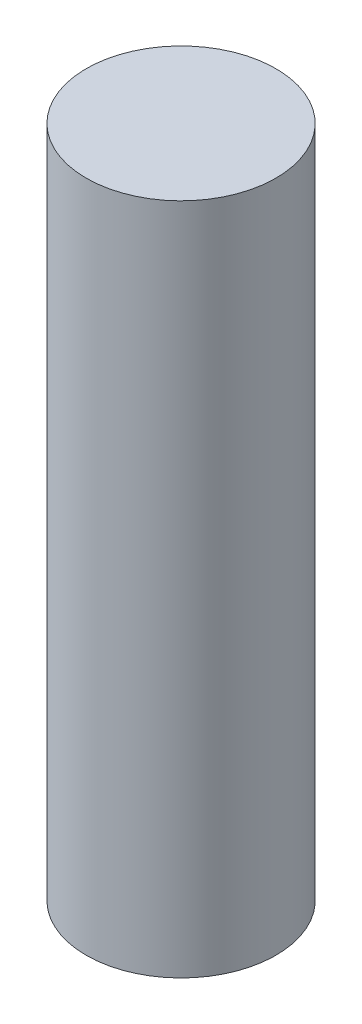
SolidWorks part; units mm, degrees
ref_plane "Front Plane" through (0, 0, 0) normal (0, 0, 1) x (1, 0, 0)
ref_plane "Top Plane" through (0, 0, 0) normal (0, 1, 0) x (1, 0, 0)
ref_plane "Right Plane" through (0, 0, 0) normal (1, 0, 0) x (0, 0, -1)
sketch "Sketch1" plane through (0, 0, 0) normal (0, 1, 0) x (1, 0, 0)
  circle A0 centre (0, 0) radius 4.75
  dimension "D1" = 9.5
extrude "Boss-Extrude1" add sketch "Sketch1" along normal blind 33.7
sketch "Sketch2" plane through (0, 0, 0) normal (0, -1, 0) x (1, 0, 0)
  circle A0 centre (0, 0) radius 3.25
  circle A1 centre (0, 0) radius 4.75 construction
  dimension "D1" = 1.5
extrude "Cut-Extrude1" cut sketch "Sketch2" against normal blind 17
